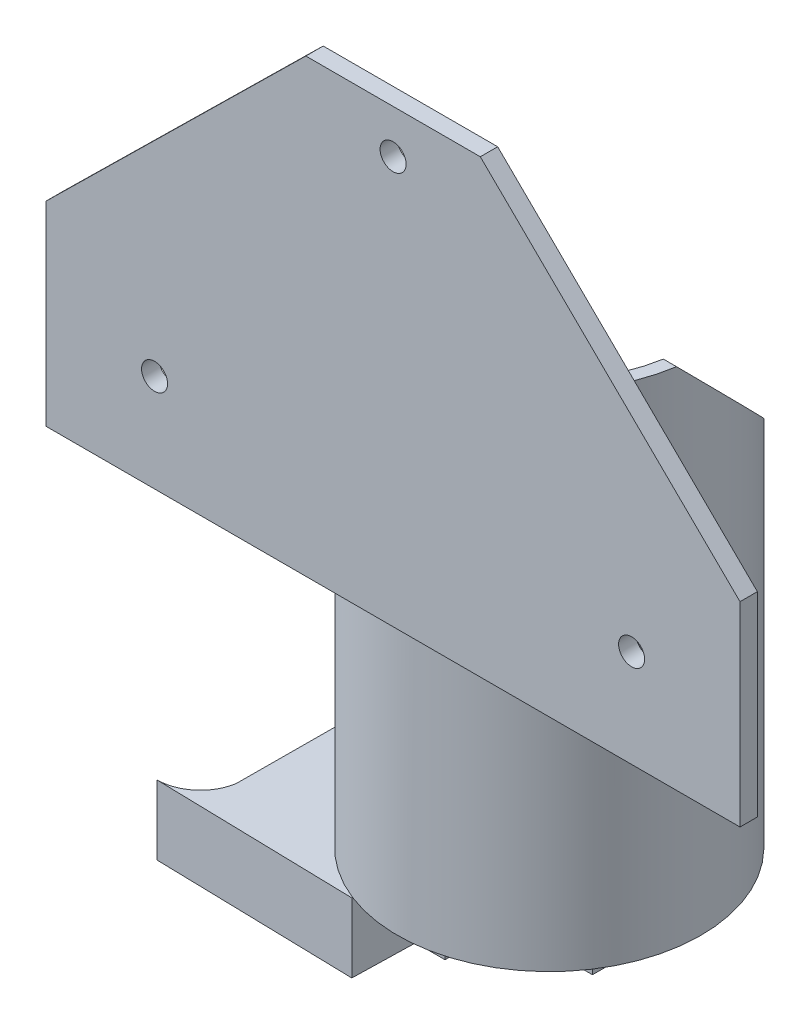
SolidWorks part; units mm, degrees
ref_plane "Front Plane" through (0, 0, 0) normal (0, 0, 1) x (1, 0, 0)
ref_plane "Top Plane" through (0, 0, 0) normal (0, 1, 0) x (1, 0, 0)
ref_plane "Right Plane" through (0, 0, 0) normal (1, 0, 0) x (0, 0, -1)
sketch "Sketch1" plane through (0, 0, 0) normal (0, 1, 0) x (1, 0, 0)
  circle A0 centre (0, 0) radius 17.5
  dimension "D1" = 35
extrude "Boss-Extrude1" add sketch "Sketch1" along normal blind 53 and the other way blind 5
sketch "Sketch2" plane through (0, 53, 0) normal (0, 1, 0) x (1, 0, 0)
  circle A0 centre (0, 0) radius 16
extrude "Cut-Extrude1" cut sketch "Sketch2" against normal blind 108
sketch "Sketch3" plane through (0, 53, 0) normal (0, 1, 0) x (1, 0, 0)
  line L1 (-12.5, 6) -> (12.5, 6)
  line L2 (-12.5, 6) -> (-12.5, 26)
  line L3 (-12.5, 26) -> (12.5, 26)
  line L4 (12.5, 6) -> (12.5, 26)
  line L5 (-12.5, 6) -> (12.5, 26) construction
  line L6 (-12.5, 26) -> (12.5, 6) construction
  circle A0 centre (0, 0) radius 16 construction
  point P0 (0, 16)
extrude "Cut-Extrude2" cut sketch "Sketch3" against normal blind 108
sketch "Sketch7" plane through (0, 0, 0) normal (1, 0, 0) x (0, 0, -1)
  line L0 (12.2474, 53) -> (12.2474, 38)
  line L1 (12.2474, -5) -> (12.2474, 53) construction
  line L2 (12.2474, 38) -> (-2.6263, 53)
  line L3 (12.2474, 53) -> (-17.5, 53) construction
  line L4 (-2.6263, 53) -> (12.2474, 53)
extrude "Cut-Extrude3" cut sketch "Sketch7" against normal blind 108 and the other way blind 108
ref_plane "Plane1" through (0, 0, 18) normal (0, 0, 1) x (1, 0, 0)
sketch "Sketch8" plane through (0, 0, 18) normal (0, 0, 1) x (1, 0, 0)
  line L1 (10.0571, 78.0232) -> (40, 48.5711)
  line L2 (40, 48.5711) -> (40, 26.0711)
  line L3 (40, 26.0711) -> (0, 26.0711)
  line L5 (0, -16.3611) -> (0, 16.3611) construction
  line L7 (-40, 26.0711) -> (0, 26.0711)
  line L8 (-40, 48.5711) -> (-40, 26.0711)
  line L9 (-10.0571, 78.0232) -> (-40, 48.5711)
  line L11 (-10.0571, 78.0232) -> (10.0571, 78.0232)
extrude "Boss-Extrude2" add sketch "Sketch8" against normal blind 2
sketch "Sketch10" plane through (0, 0, 16) normal (0, 0, -1) x (-1, 0, 0)
  line L0 (0, 53) -> (0, 73) construction
  line L1 (-17.5, 37.3211) -> (-27.5, 37.3211) construction
  line L2 (-17.5, 50.3514) -> (-17.5, -5) construction
  line L3 (17.5, 37.3211) -> (27.5, 37.3211) construction
  line L4 (17.5, -5) -> (17.5, 50.3514) construction
  circle A0 centre (-27.5, 37.3211) radius 1.5
  circle A1 centre (27.5, 37.3211) radius 1.5
  circle A2 centre (0, 73) radius 1.5
extrude "Cut-Extrude4" cut sketch "Sketch10" against normal blind 16
sketch "Sketch11" plane through (0, -5, 0) normal (0, -1, 0) x (1, 0, 0)
  line L11 (-6.3909, -8.8634) -> (-6.4802, -11.761)
  line L12 (-6.0124, 1.1829) -> (-6.3909, -8.8634)
  line L13 (-6.3756, 16.3864) -> (-6.0124, 1.1829)
  line L14 (-29.3909, 15.8366) -> (-6.3756, 16.3864)
  line L15 (-24.3909, -0.2751) -> (-24.4524, 11.6188)
  line L16 (-28.8909, -16.8634) -> (-31.8909, -16.8634)
  line L17 (-28.8909, -23.8634) -> (-28.8909, -16.8634)
  line L18 (-18.8909, -23.8634) -> (-28.8909, -23.8634)
  line L19 (-18.8909, -26.8634) -> (-18.8909, -23.8634)
  line L20 (-10.2759, -26.8054) -> (-18.8909, -26.8634)
  arc A5 (-6.4802, -11.761) -> (-8.7246, -13.0297) centre (-8.2368, -11.2731) cw
  arc A6 (-24.4524, 11.6188) -> (-29.3909, 15.8366) centre (-29.3908, 10.8366) ccw
  arc A7 (-31.8909, -16.8634) -> (-24.3909, -0.2751) centre (-9.7961, -16.8634) cw
  arc A8 (-9.9319, -25.1296) -> (-10.2759, -26.8054) centre (-10.9418, -25.7955) cw
  arc A9 (-9.9319, -25.1296) -> (-8.7246, -13.0297) centre (-6.3756, -19.3742) cw
extrude "Boss-Extrude3" add sketch "Sketch11" along normal blind 8
sketch "Sketch12" plane through (0, -13, 0) normal (0, -1, 0) x (1, 0, 0)
  line L17 (-31.8909, -26.8634) -> (-18.8909, -26.8634)
  line L18 (-31.8909, -16.8634) -> (-31.8909, -26.8634)
  line L19 (-28.8909, -16.8634) -> (-31.8909, -16.8634)
  line L20 (-28.8909, -23.8634) -> (-28.8909, -16.8634)
  line L21 (-18.8909, -23.8634) -> (-28.8909, -23.8634)
  line L22 (-18.8909, -26.8634) -> (-18.8909, -23.8634)
extrude "Boss-Extrude5" add sketch "Sketch12" along normal blind 18 and the other way blind 4 separate body
sketch "Sketch13" plane through (0, -31, 0) normal (0, -1, 0) x (1, 0, 0)
  line L7 (-44.3227, -26.8076) -> (-18.8227, -26.8076)
  line L8 (-44.3227, -16.8076) -> (-44.3227, -26.8076)
  line L9 (-28.8227, -16.8076) -> (-44.3227, -16.8076)
  line L10 (-28.8227, -23.8076) -> (-28.8227, -16.8076)
  line L11 (-18.8227, -23.8076) -> (-28.8227, -23.8076)
  line L12 (-18.8227, -26.8076) -> (-18.8227, -23.8076)
  circle A1 centre (-39.936, -19.6077) radius 1.5002
extrude "Boss-Extrude6" add sketch "Sketch13" along normal blind 8
